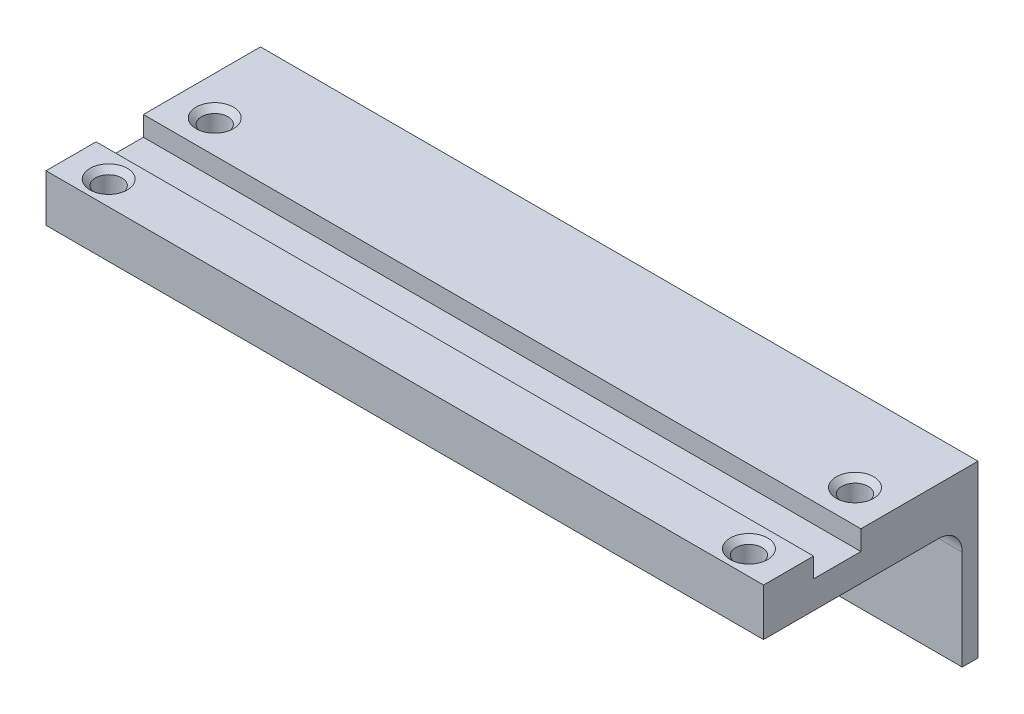
SolidWorks part; units mm, degrees
ref_plane "Front Plane" through (0, 0, 0) normal (0, 0, 1) x (1, 0, 0)
ref_plane "Top Plane" through (0, 0, 0) normal (0, 1, 0) x (1, 0, 0)
ref_plane "Right Plane" through (0, 0, 0) normal (1, 0, 0) x (0, 0, -1)
sketch "Sketch1" plane through (0, 0, 0) normal (0, 1, 0) x (1, 0, 0)
  line L5 (-45.5, 12) -> (45.5, 12)
  line L6 (-45.5, 12) -> (-45.5, -12)
  line L7 (-45.5, -12) -> (45.5, -12)
  line L8 (45.5, 12) -> (45.5, -12)
  line L9 (-45.5, 12) -> (45.5, -12) construction
  line L10 (-45.5, -12) -> (45.5, 12) construction
  point P0 (0, 0)
  dimension "D1" = 91
  dimension "D2" = 24
extrude "Boss-Extrude1" add sketch "Sketch1" along normal blind 4
sketch "Sketch2" plane through (0, 4, 0) normal (0, 1, 0) x (1, 0, 0)
  circle A0 centre (-40.6, 3.5) radius 1.675
  circle A2 centre (-40.6, -9.95) radius 1.675
  circle A3 centre (40.6, 3.5) radius 1.675
  circle A4 centre (40.6, -9.95) radius 1.675
  line B0 (-42.6, 12) -> (-42.6, -12)
  line B1 (-42.6, -12) -> (42.6, -12)
  line B2 (42.6, -12) -> (42.6, 12)
  line B3 (42.6, 12) -> (-42.6, 12)
  line B4 (-42.6, 0) -> (42.6, 0) construction
  line B5 (0, 12) -> (0, -12) construction
  arc B6 (41.75, -9.95) -> (39.45, -9.95) centre (40.6, -9.95) ccw
  arc B7 (39.45, -9.95) -> (41.75, -9.95) centre (40.6, -9.95) ccw
  arc B8 (41.75, 3.5) -> (39.45, 3.5) centre (40.6, 3.5) ccw
  arc B9 (39.45, 3.5) -> (41.75, 3.5) centre (40.6, 3.5) ccw
  arc B10 (11.65, 3.5) -> (9.35, 3.5) centre (10.5, 3.5) ccw
  arc B11 (9.35, 3.5) -> (11.65, 3.5) centre (10.5, 3.5) ccw
  arc B12 (11.65, -9.95) -> (9.35, -9.95) centre (10.5, -9.95) ccw
  arc B13 (9.35, -9.95) -> (11.65, -9.95) centre (10.5, -9.95) ccw
  arc B14 (-39.45, -9.95) -> (-41.75, -9.95) centre (-40.6, -9.95) ccw
  arc B15 (-41.75, -9.95) -> (-39.45, -9.95) centre (-40.6, -9.95) ccw
  arc B16 (-39.45, 3.5) -> (-41.75, 3.5) centre (-40.6, 3.5) ccw
  arc B17 (-41.75, 3.5) -> (-39.45, 3.5) centre (-40.6, 3.5) ccw
  arc B18 (-22.05, -3.65) -> (-20.55, -3.65) centre (-21.3, -3.65) ccw
  arc B19 (-20.55, -3.65) -> (-22.05, -3.65) centre (-21.3, -3.65) ccw
  arc B20 (-9.35, -9.95) -> (-11.65, -9.95) centre (-10.5, -9.95) ccw
  arc B21 (-11.65, -9.95) -> (-9.35, -9.95) centre (-10.5, -9.95) ccw
  arc B22 (20.55, -3.65) -> (22.05, -3.65) centre (21.3, -3.65) ccw
  arc B23 (22.05, -3.65) -> (20.55, -3.65) centre (21.3, -3.65) ccw
  arc B24 (-39.55, -3.65) -> (-38.05, -3.65) centre (-38.8, -3.65) ccw
  arc B25 (-38.05, -3.65) -> (-39.55, -3.65) centre (-38.8, -3.65) ccw
  arc B26 (38.05, -3.65) -> (39.55, -3.65) centre (38.8, -3.65) ccw
  arc B27 (39.55, -3.65) -> (38.05, -3.65) centre (38.8, -3.65) ccw
  arc B28 (-11.65, 3.5) -> (-9.35, 3.5) centre (-10.5, 3.5) ccw
  arc B29 (-9.35, 3.5) -> (-11.65, 3.5) centre (-10.5, 3.5) ccw
  dimension "D1" = 3.35
  dimension "D2" = 3.35
  dimension "D3" = 3.35
  dimension "D4" = 3.35
sketch_block_instance "Block2-2"
sketch_block "Block2"
extrude "Cut-Extrude1" cut sketch "Sketch2" against normal through all contours A2 | A4 | A0 | A3
sketch "Sketch3" plane through (0, 4, 0) normal (0, 1, 0) x (1, 0, 0)
  line L0 (-45.5, 12) -> (-45.5, -12) construction
  line L1 (-45.5, -0.65) -> (45.5, -0.65)
  line L2 (-45.5, -0.65) -> (-45.5, -6.65)
  line L3 (-45.5, -6.65) -> (45.5, -6.65)
  line L4 (45.5, -0.65) -> (45.5, -6.65)
  line L5 (45.5, -12) -> (45.5, 12) construction
  line L6 (-45.5, -3.65) -> (45.5, -3.65) construction
  line L7 (-38.8, -3.65) -> (-21.3, -3.65) construction
  line B0 (-42.6, 12) -> (-42.6, -12)
  line B1 (-42.6, -12) -> (42.6, -12)
  line B2 (42.6, -12) -> (42.6, 12)
  line B3 (42.6, 12) -> (-42.6, 12)
  line B4 (-42.6, 0) -> (42.6, 0) construction
  line B5 (0, 12) -> (0, -12) construction
  arc B6 (41.75, -9.95) -> (39.45, -9.95) centre (40.6, -9.95) ccw
  arc B7 (39.45, -9.95) -> (41.75, -9.95) centre (40.6, -9.95) ccw
  arc B8 (41.75, 3.5) -> (39.45, 3.5) centre (40.6, 3.5) ccw
  arc B9 (39.45, 3.5) -> (41.75, 3.5) centre (40.6, 3.5) ccw
  arc B10 (11.65, 3.5) -> (9.35, 3.5) centre (10.5, 3.5) ccw
  arc B11 (9.35, 3.5) -> (11.65, 3.5) centre (10.5, 3.5) ccw
  arc B12 (11.65, -9.95) -> (9.35, -9.95) centre (10.5, -9.95) ccw
  arc B13 (9.35, -9.95) -> (11.65, -9.95) centre (10.5, -9.95) ccw
  arc B14 (-39.45, -9.95) -> (-41.75, -9.95) centre (-40.6, -9.95) ccw
  arc B15 (-41.75, -9.95) -> (-39.45, -9.95) centre (-40.6, -9.95) ccw
  arc B16 (-39.45, 3.5) -> (-41.75, 3.5) centre (-40.6, 3.5) ccw
  arc B17 (-41.75, 3.5) -> (-39.45, 3.5) centre (-40.6, 3.5) ccw
  arc B18 (-22.05, -3.65) -> (-20.55, -3.65) centre (-21.3, -3.65) ccw
  arc B19 (-20.55, -3.65) -> (-22.05, -3.65) centre (-21.3, -3.65) ccw
  arc B20 (-9.35, -9.95) -> (-11.65, -9.95) centre (-10.5, -9.95) ccw
  arc B21 (-11.65, -9.95) -> (-9.35, -9.95) centre (-10.5, -9.95) ccw
  arc B22 (20.55, -3.65) -> (22.05, -3.65) centre (21.3, -3.65) ccw
  arc B23 (22.05, -3.65) -> (20.55, -3.65) centre (21.3, -3.65) ccw
  arc B24 (-39.55, -3.65) -> (-38.05, -3.65) centre (-38.8, -3.65) ccw
  arc B25 (-38.05, -3.65) -> (-39.55, -3.65) centre (-38.8, -3.65) ccw
  arc B26 (38.05, -3.65) -> (39.55, -3.65) centre (38.8, -3.65) ccw
  arc B27 (39.55, -3.65) -> (38.05, -3.65) centre (38.8, -3.65) ccw
  arc B28 (-11.65, 3.5) -> (-9.35, 3.5) centre (-10.5, 3.5) ccw
  arc B29 (-9.35, 3.5) -> (-11.65, 3.5) centre (-10.5, 3.5) ccw
  dimension "D1" = 6
sketch_block_instance "Block2-3"
extrude "Cut-Extrude2" cut sketch "Sketch3" against normal blind 2.5 contours L2 L1 L4 L3
sketch "Sketch4" plane through (0, 0, -12) normal (0, 0, -1) x (-1, 0, 0)
  line L1 (-45.5, 4) -> (45.5, 4)
  line L2 (-45.5, 4) -> (-45.5, 0)
  line L3 (-45.5, 0) -> (45.5, 0)
  line L4 (45.5, 4) -> (45.5, 0)
extrude "Boss-Extrude2" add sketch "Sketch4" along normal blind 2.2
sketch "Sketch5" plane through (0, 0, 0) normal (0, -1, 0) x (1, 0, 0)
  line L0 (45.5, 12) -> (45.5, -14.2) construction
  line L1 (-45.5, -14.2) -> (45.5, -14.2)
  line L2 (-45.5, -14.2) -> (-45.5, -12.2)
  line L3 (-45.5, -12.2) -> (45.5, -12.2)
  line L4 (45.5, -14.2) -> (45.5, -12.2)
  dimension "D1" = 2
extrude "Boss-Extrude3" add sketch "Sketch5" along normal blind 17.62
sketch "Sketch6" plane through (0, 0, -12.2) normal (0, 0, 1) x (1, 0, 0)
  line L0 (0, -17.62) -> (0, -10.12) construction
  line L1 (45.5, -17.62) -> (-45.5, -17.62) construction
  line L2 (0, -10.12) -> (21.25, -10.12) construction
  line L3 (0, -10.12) -> (-21.25, -10.12) construction
  circle A0 centre (-21.25, -10.12) radius 1.75
  circle A1 centre (0, -10.12) radius 1.75
  circle A2 centre (21.25, -10.12) radius 1.75
  dimension "D4" = 3.5
  dimension "D5" = 3.5
  dimension "D6" = 3.5
  dimension "D1" = 21.25
  dimension "D2" = 21.25
  dimension "D3" = 7.5
extrude "Cut-Extrude3" cut sketch "Sketch6" against normal through all
sketch "Sketch7" plane through (0, 0, 0) normal (0, -1, 0) x (1, 0, 0)
  line L4 (-45.5, -12.2) -> (45.5, -12.2)
  line L5 (45.5, -12.2) -> (45.5, 12)
  line L6 (45.5, 12) -> (-45.5, 12)
  line L7 (-45.5, 12) -> (-45.5, -12.2)
  line L8 (-45.5, -12.2) -> (45.5, -12.2)
  line L9 (45.5, -12.2) -> (45.5, 12)
  line L10 (45.5, 12) -> (-45.5, 12)
  line L11 (-45.5, 12) -> (-45.5, -12.2)
  circle A0 centre (40.6, 9.95) radius 1.675 construction
  circle A1 centre (40.6, -3.5) radius 1.675 construction
  circle A2 centre (-40.6, -3.5) radius 1.675 construction
  circle A3 centre (-40.6, 9.95) radius 1.675 construction
  circle A4 centre (40.6, 9.95) radius 1.675
  circle A5 centre (40.6, -3.5) radius 1.675
  circle A6 centre (-40.6, -3.5) radius 1.675
  circle A7 centre (-40.6, 9.95) radius 1.675
  dimension "D1" = 0
extrude "Boss-Extrude5" add sketch "Sketch7" along normal blind 2
sketch "Sketch8" plane through (0, 0, 12) normal (0, 0, 1) x (1, 0, 0)
  line L6 (45.5, 4) -> (-45.5, 4)
  line L8 (-45.5, 4) -> (-45.5, -2)
  line L9 (-45.5, -2) -> (45.5, -2)
  line L10 (45.5, -2) -> (45.5, 4)
  line L12 (45.5, 4) -> (-45.5, 4)
  line L14 (-45.5, 4) -> (-45.5, -2)
  line L15 (-45.5, -2) -> (45.5, -2)
  line L16 (45.5, -2) -> (45.5, 4)
  dimension "D1" = 0
extrude "Boss-Extrude6" add sketch "Sketch8" along normal blind 1
chamfer "Chamfer1" distance 0.7 angle 45 4 edges at (40.6, 4, 11.625) (-40.6, 4, -1.825) (40.6, 4, -1.825) (-40.6, 4, 11.625)
fillet "Fillet1" radius 3 1 edges at (0, -2, -12.2)
